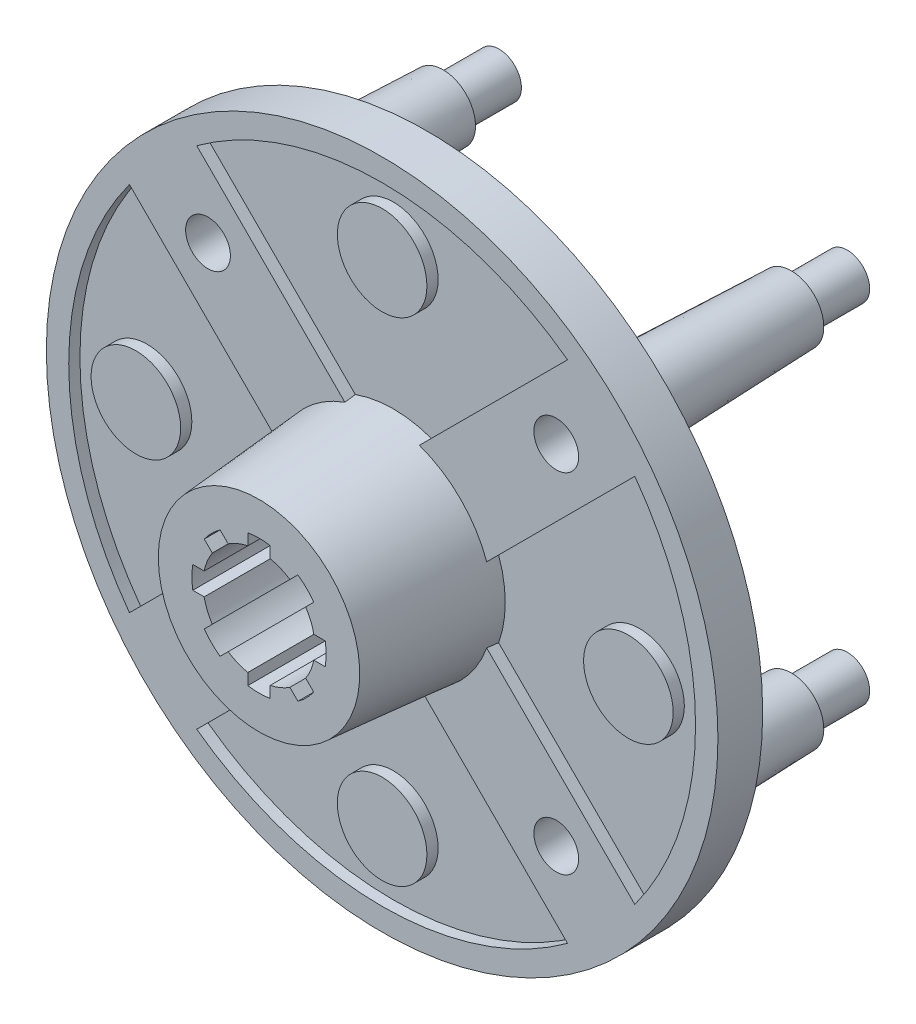
SolidWorks part; units mm, degrees
ref_plane "前视基准面" through (0, 0, 0) normal (0, 0, 1) x (1, 0, 0)
ref_plane "上视基准面" through (0, 0, 0) normal (0, 1, 0) x (1, 0, 0)
ref_plane "右视基准面" through (0, 0, 0) normal (1, 0, 0) x (0, 0, -1)
sketch "草图1" plane through (0, 0, 0) normal (0, 0, 1) x (1, 0, 0)
  circle A0 centre (0, 0) radius 30
  dimension "D1" = 60
extrude "凸台-拉伸1" add sketch "草图1" along normal blind 4
sketch "草图2" plane through (0, 0, 4) normal (0, 0, 1) x (1, 0, 0)
  circle A4 centre (0, 0) radius 28
  circle A5 centre (0, 0) radius 28
  dimension "D2" = 2
extrude "切除-拉伸1" cut sketch "草图2" against normal blind 1
sketch "草图3" plane through (0, 0, 3) normal (0, 0, 1) x (1, 0, 0)
  line L0 (0, 0) -> (-19.799, 19.799)
  line L1 (0, -2.2) -> (0, 2.2) construction
  circle A0 centre (0, 0) radius 28 construction
  dimension "D1" = 45
extrude "拉伸-薄壁1" add sketch "草图3" along normal blind 1 thin thin type mid plane wall 8.5
pattern_circular "阵列(圆周)1" count 4 over 360 about axis through (0, 0, 0) along (0, 0, 1) of "拉伸-薄壁1"
sketch "草图4" plane through (0, 0, 3) normal (0, 0, 1) x (1, 0, 0)
  circle A0 centre (0, 0) radius 10
  dimension "D1" = 20
ref_plane "基准面1" through (0, 0, 15) normal (0, 0, -1) x (-1, 0, 0)
sketch "草图5" plane through (0, 0, 15) normal (0, 0, -1) x (-1, 0, 0)
  circle A0 centre (0, 0) radius 9
  dimension "D1" = 18
loft "放样1" add profiles "草图4", "草图5"
sketch "草图6" plane through (0, 0, 3) normal (0, 0, 1) x (1, 0, 0)
  line L0 (0, -8.2501) -> (0, 8.2501) construction
  line L1 (8.2501, 0) -> (-8.2501, 0) construction
  circle A0 centre (0, 22) radius 4
  dimension "D1" = 8
  dimension "D2" = 22
extrude "凸台-拉伸2" add sketch "草图6" along normal blind 1 and the other way blind 6
sketch "草图8" plane through (0, 0, -3) normal (0, 0, -1) x (-1, 0, 0)
  circle A0 centre (0, 22) radius 2.5
  dimension "D1" = 5
extrude "切除-拉伸2" cut sketch "草图8" against normal blind 4
pattern_circular "阵列(圆周)2" count 4 over 360 about axis through (0, 0, 0) along (0, 0, 1) of "凸台-拉伸2", "切除-拉伸2"
sketch "草图9" plane through (0, 0, 4) normal (0, 0, 1) x (1, 0, 0)
  line L0 (-8.112, 8.112) -> (-17.4827, 17.4827) construction
  line L1 (-3.3955, 9.4059) -> (-16.5644, 22.5748) construction
  line L2 (-9.3407, 3.3303) -> (-22.5748, 16.5644) construction
  circle A0 centre (-15.5563, 15.5563) radius 2
  point P8 (-17.4827, 17.4827)
  point P9 (-14.4485, 14.3782)
  point P10 (-16.4585, 13.5633)
  dimension "D1" = 4
  dimension "D2" = 22
extrude "切除-拉伸3" cut sketch "草图9" against normal through all
pattern_circular "阵列(圆周)3" count 4 over 360 about axis through (0, 0, 0) along (0, 0, 1) of "切除-拉伸3"
sketch "草图10" plane through (0, 0, 15) normal (0, 0, 1) x (1, 0, 0)
  circle A0 centre (0, 0) radius 5
  dimension "D1" = 10
extrude "切除-拉伸4" cut sketch "草图10" against normal through all
sketch "草图11" plane through (0, 0, 15) normal (0, 0, 1) x (1, 0, 0)
  line L0 (0, -6) -> (0, 6) construction
  line L1 (0, -9.9001) -> (0, 9.9001) construction
  line L3 (1, -5.9161) -> (1, 5.9161)
  line L4 (-1, -5.9161) -> (-1, 5.9161)
  line L5 (1, -6) -> (1, 6) construction
  line L6 (-1, -6) -> (-1, 6) construction
  arc A0 (-1, -5.9161) -> (1, -5.9161) centre (0, 0) ccw
  arc A1 (1, 5.9161) -> (-1, 5.9161) centre (0, 0) ccw
  point P9 (0, 0)
  dimension "D2" = 1
  dimension "D1" = 12
  dimension "D3" = 1
extrude "切除-拉伸5" cut sketch "草图11" against normal through all
pattern_circular "阵列(圆周)4" count 8 over 360 about axis through (0, 0, 0) along (0, 0, 1) of "切除-拉伸5"
sketch "草图12" plane through (0, 0, 0) normal (0, 0, -1) x (-1, 0, 0)
  line L0 (0, 0) -> (-35.3878, 35.3878) construction
  line L1 (0, 9.9001) -> (0, -9.9001) construction
  circle A0 centre (-15.5563, 15.5563) radius 3.5
  point P7 (0, 0)
  dimension "D2" = 7
  dimension "D1" = 45
  dimension "D3" = 22
ref_plane "基准面2" through (0, 0, -17) normal (0, 0, -1) x (-1, 0, 0)
sketch "草图13" plane through (0, 0, -17) normal (0, 0, -1) x (-1, 0, 0)
  circle A0 centre (-15.5563, 15.5563) radius 2.9
  dimension "D1" = 5.8
loft "放样2" add profiles "草图12", "草图13"
sketch "草图14" plane through (0, 0, -17) normal (0, 0, -1) x (-1, 0, 0)
  circle A0 centre (-15.5563, 15.5563) radius 2
  dimension "D1" = 4
extrude "凸台-拉伸3" add sketch "草图14" along normal blind 5
sketch "草图15" plane through (0, 0, -22) normal (0, 0, -1) x (-1, 0, 0)
  circle A0 centre (-15.5563, 15.5563) radius 1.5
  dimension "D1" = 3
extrude "切除-拉伸6" cut sketch "草图15" against normal blind 3
pattern_circular "阵列(圆周)5" count 4 over 360 about axis through (0, 0, 0) along (0, 0, 1) of "放样2", "凸台-拉伸3", "切除-拉伸6"
